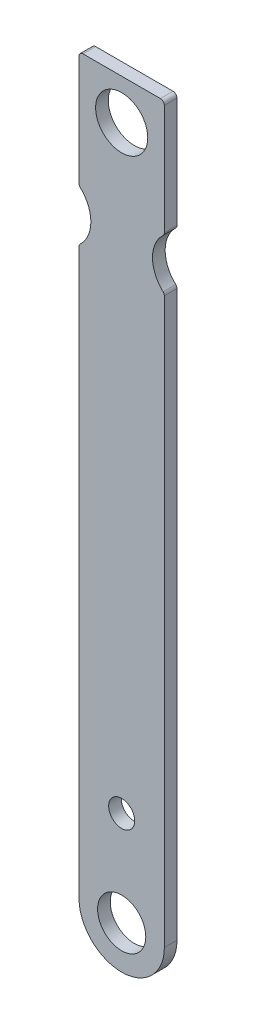
SolidWorks part; units mm, degrees
ref_plane "Front" through (0, 0, 0) normal (0, 0, 1) x (1, 0, 0)
ref_plane "Top" through (0, 0, 0) normal (0, 1, 0) x (1, 0, 0)
ref_plane "Right" through (0, 0, 0) normal (1, 0, 0) x (0, 0, -1)
sketch "草图2" plane through (0, 0, 0) normal (0, 0, 1) x (1, 0, 0)
  line L20 (2.45, 46.401) -> (-2.45, 46.401)
  line L21 (-2.7, 46.151) -> (-2.7, 39.1693)
  line L22 (-2.7, 35.7147) -> (-2.7, 0)
  line L23 (2.7, 0) -> (2.7, 35.7147)
  line L24 (2.7, 39.1693) -> (2.7, 46.151)
  circle A0 centre (0, 0) radius 1.525
  circle A1 centre (0, 6) radius 0.825
  circle A2 centre (0, 43.851) radius 1.65
  circle A3 centre (0, 43.851) radius 1.6 construction
  circle A4 centre (0, 6) radius 1 construction
  circle A5 centre (0, 0) radius 1.51 construction
  arc A42 (2.7, 46.151) -> (2.45, 46.401) centre (2.45, 46.151) ccw
  arc A43 (-2.45, 46.401) -> (-2.7, 46.151) centre (-2.45, 46.151) ccw
  arc A44 (-2.7, 39.1693) -> (-2.6207, 38.9866) centre (-2.45, 39.1693) ccw
  arc A45 (-2.6207, 35.8974) -> (-2.6207, 38.9866) centre (-4.064, 37.442) ccw
  arc A46 (-2.6207, 35.8974) -> (-2.7, 35.7147) centre (-2.45, 35.7147) ccw
  arc A47 (-2.7, 0) -> (2.7, 0) centre (0, 0) ccw
  arc A48 (2.7, 35.7147) -> (2.6207, 35.8974) centre (2.45, 35.7147) ccw
  arc A49 (2.6207, 38.9866) -> (2.6207, 35.8974) centre (4.064, 37.442) ccw
  arc A50 (2.6207, 38.9866) -> (2.7, 39.1693) centre (2.45, 39.1693) ccw
  dimension "D2" = 3.05
  dimension "D3" = 1.65
  dimension "D4" = 3.3
  dimension "D1" = 5.4
extrude "凸台-拉伸1" add sketch "草图2" along normal blind 0.8
